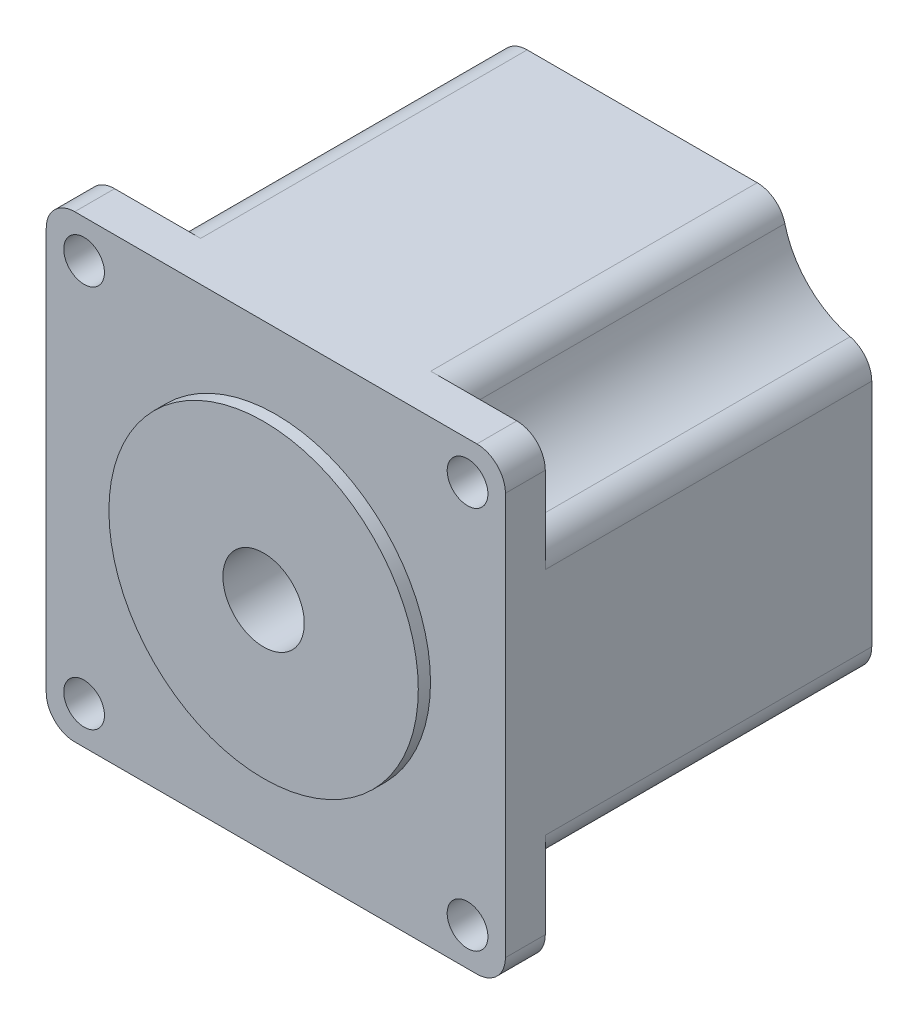
SolidWorks part; units mm, degrees
material "Plain Carbon Steel"
ref_plane "Front" through (0, 0, 0) normal (0, 0, 1) x (1, 0, 0)
ref_plane "Top" through (0, 0, 0) normal (0, 1, 0) x (1, 0, 0)
ref_plane "Right" through (0, 0, 0) normal (1, 0, 0) x (0, 0, -1)
sketch "Sketch1" plane through (0, 0, 0) normal (0, 0, 1) x (1, 0, 0)
  line L1 (-24.7, -28.2) -> (24.7, -28.2)
  line L2 (-28.2, -24.7) -> (-28.2, 24.7)
  line L3 (-24.7, 28.2) -> (24.7, 28.2)
  line L4 (28.2, -24.7) -> (28.2, 24.7)
  line L5 (-28.2, -28.2) -> (28.2, 28.2) construction
  line L6 (-28.2, 28.2) -> (28.2, -28.2) construction
  circle A0 centre (0, 0) radius 5
  arc A1 (-28.2, 24.7) -> (-24.7, 28.2) centre (-24.7, 24.7) cw
  arc A2 (-24.7, -28.2) -> (-28.2, -24.7) centre (-24.7, -24.7) cw
  arc A3 (24.7, -28.2) -> (28.2, -24.7) centre (24.7, -24.7) ccw
  arc A4 (24.7, 28.2) -> (28.2, 24.7) centre (24.7, 24.7) cw
  point P0 (0, 0)
  dimension "D3" = 10
  dimension "D4" = 3.5
  dimension "D1" = 56.4
  dimension "D2" = 56.4
extrude "Boss-Extrude1" add sketch "Sketch1" along normal blind 45
sketch "Sketch2" plane through (0, 0, 45) normal (0, 0, 1) x (1, 0, 0)
  circle A0 centre (0, 0) radius 19
  circle A1 centre (0, 0) radius 5
  dimension "D1" = 38
  dimension "D2" = 10
extrude "Boss-Extrude2" add sketch "Sketch2" along normal blind 1.5
sketch "Sketch3" plane through (0, 0, 45) normal (0, 0, 1) x (1, 0, 0)
  line L1 (-23.55, 23.55) -> (23.55, 23.55)
  line L2 (-23.55, 23.55) -> (-23.55, -23.55)
  line L3 (-23.55, -23.55) -> (23.55, -23.55)
  line L4 (23.55, 23.55) -> (23.55, -23.55)
  line L5 (-23.55, 23.55) -> (23.55, -23.55) construction
  line L6 (-23.55, -23.55) -> (23.55, 23.55) construction
  circle A0 centre (-23.55, 23.55) radius 2.5
  circle A1 centre (23.55, 23.55) radius 2.5
  circle A2 centre (23.55, -23.55) radius 2.5
  circle A3 centre (-23.55, -23.55) radius 2.5
  point P0 (0, 0)
  dimension "D3" = 5
  dimension "D4" = 5
  dimension "D5" = 5
  dimension "D6" = 5
  dimension "D1" = 47.1
  dimension "D2" = 47.1
extrude "Cut-Extrude1" cut sketch "Sketch3" against normal through all contours A0 | A1 | A2 | A3
sketch "Sketch4" plane through (0, 0, 0) normal (0, 0, -1) x (-1, 0, 0)
  line L0 (28.2, 17.2) -> (28.2, -17.2)
  line L1 (-28.2, -24.7) -> (-28.2, 24.7) construction
  line L2 (-17.2, 28.2) -> (17.2, 28.2)
  line L3 (-24.7, 28.2) -> (24.7, 28.2) construction
  line L4 (17.2, -28.2) -> (-17.2, -28.2)
  line L5 (28.2, 24.7) -> (28.2, -24.7) construction
  line L6 (-28.2, -17.2) -> (-28.2, 17.2)
  line L8 (-17.2, 28.2) -> (-28.2, 28.2)
  line L9 (-28.2, 28.2) -> (-28.2, 17.2)
  line L10 (-28.2, -17.2) -> (-28.2, -28.2)
  line L11 (-28.2, -28.2) -> (-17.2, -28.2)
  line L12 (17.2, -28.2) -> (28.2, -28.2)
  line L13 (28.2, -28.2) -> (28.2, -17.2)
  line L14 (28.2, 17.2) -> (28.2, 28.2)
  line L15 (28.2, 28.2) -> (17.2, 28.2)
  arc A0 (-28.2, 17.2) -> (-17.2, 28.2) centre (-28.2, 28.2) ccw
  arc A1 (-28.2, -17.2) -> (-17.2, -28.2) centre (-28.2, -28.2) cw
  arc A2 (17.2, -28.2) -> (28.2, -17.2) centre (28.2, -28.2) cw
  arc A3 (17.2, 28.2) -> (28.2, 17.2) centre (28.2, 28.2) ccw
  point P17 (0, 0)
  circle M9 centre (23.55, -23.55) radius 2.5
  circle M10 centre (-23.55, -23.55) radius 2.5
  circle M11 centre (-23.55, 23.55) radius 2.5
  circle M12 centre (23.55, 23.55) radius 2.5
  arc M13 (28.2, 24.7) -> (24.7, 28.2) centre (24.7, 24.7) ccw
  line M14 (24.7, 28.2) -> (-24.7, 28.2)
  arc M15 (-24.7, 28.2) -> (-28.2, 24.7) centre (-24.7, 24.7) ccw
  line M16 (-28.2, 24.7) -> (-28.2, -24.7)
  arc M17 (-28.2, -24.7) -> (-24.7, -28.2) centre (-24.7, -24.7) ccw
  line M18 (-24.7, -28.2) -> (24.7, -28.2)
  arc M19 (24.7, -28.2) -> (28.2, -24.7) centre (24.7, -24.7) ccw
  line M20 (28.2, -24.7) -> (28.2, 24.7)
  dimension "D1" = 11
  dimension "D2" = 11
  dimension "D3" = 4
extrude "Cut-Extrude2" cut sketch "Sketch4" against normal offset from surface (40.1 mm away) 4.9 contours A0 M16 M14 M15 M11 | A1 M16 M17 M18 M10 | A2 M18 M19 M20 M9 | A3 M14 M20 M13 M12 up to face at (-21.05, -23.55, 45)
fillet "Fillet1" radius 3.5 8 edges at (28.2, -17.2, 20.05) (17.2, -28.2, 20.05) (-17.2, -28.2, 20.05) (-28.2, -17.2, 20.05) (-28.2, 17.2, 20.05) (-17.2, 28.2, 20.05) (17.2, 28.2, 20.05) (28.2, 17.2, 20.05)
